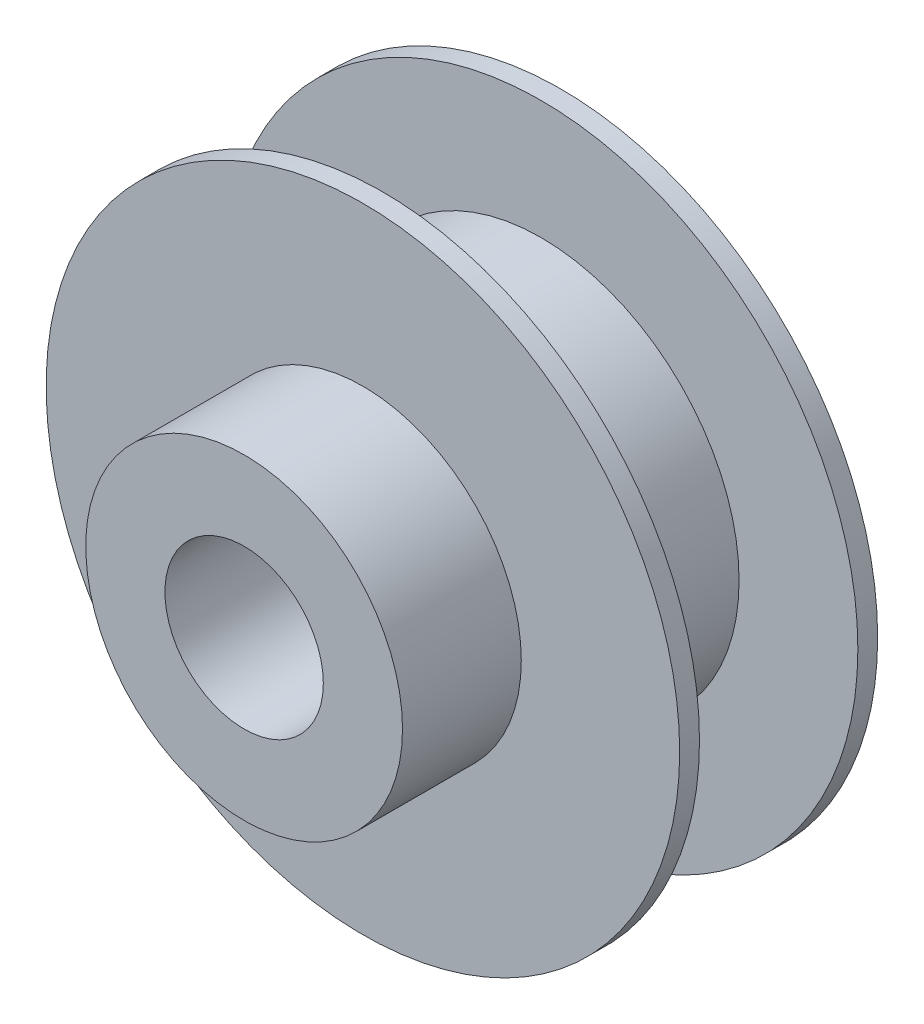
SolidWorks part; units mm, degrees
ref_plane "Plan de face" through (0, 0, 0) normal (0, 0, 1) x (1, 0, 0)
ref_plane "Plan de dessus" through (0, 0, 0) normal (0, 1, 0) x (1, 0, 0)
ref_plane "Plan de droite" through (0, 0, 0) normal (1, 0, 0) x (0, 0, -1)
sketch "Esquisse1" plane through (0, 0, 0) normal (0, 0, 1) x (1, 0, 0)
  circle A0 centre (0, 0) radius 16
  dimension "D1" = 32
extrude "Boss.-Extru.1" add sketch "Esquisse1" along normal blind 10
sketch "Esquisse2" plane through (0, 0, 10) normal (0, 0, 1) x (1, 0, 0)
  circle A0 centre (0, 0) radius 8
  dimension "D1" = 16
extrude "Boss.-Extru.2" add sketch "Esquisse2" along normal blind 6
sketch "Esquisse3" plane through (0, 0, 16) normal (0, 0, 1) x (1, 0, 0)
  circle A0 centre (0, 0) radius 4
  dimension "D1" = 8
extrude "Enlèv. mat.-Extru.1" cut sketch "Esquisse3" against normal through all
sketch "Esquisse4" plane through (0, 0, 0) normal (1, 0, 0) x (0, 0, -1)
  line L0 (0, 16) -> (-10, 16) construction
  line L1 (-9, 16) -> (-1, 16)
  line L2 (-9, 16) -> (-9, 10)
  line L3 (-9, 10) -> (-1, 10)
  line L4 (-1, 16) -> (-1, 10)
  line L5 (0, -16) -> (0, 16) construction
  line L6 (-10, 16) -> (-10, -16) construction
  line L7 (0, 0) -> (7.2899, 0) construction
  dimension "D1" = 6
  dimension "D2" = 1
  dimension "D3" = 1
revolve "Enlèvement de matière-Révolution1" cut sketch "Esquisse4" angle 360 about L7
